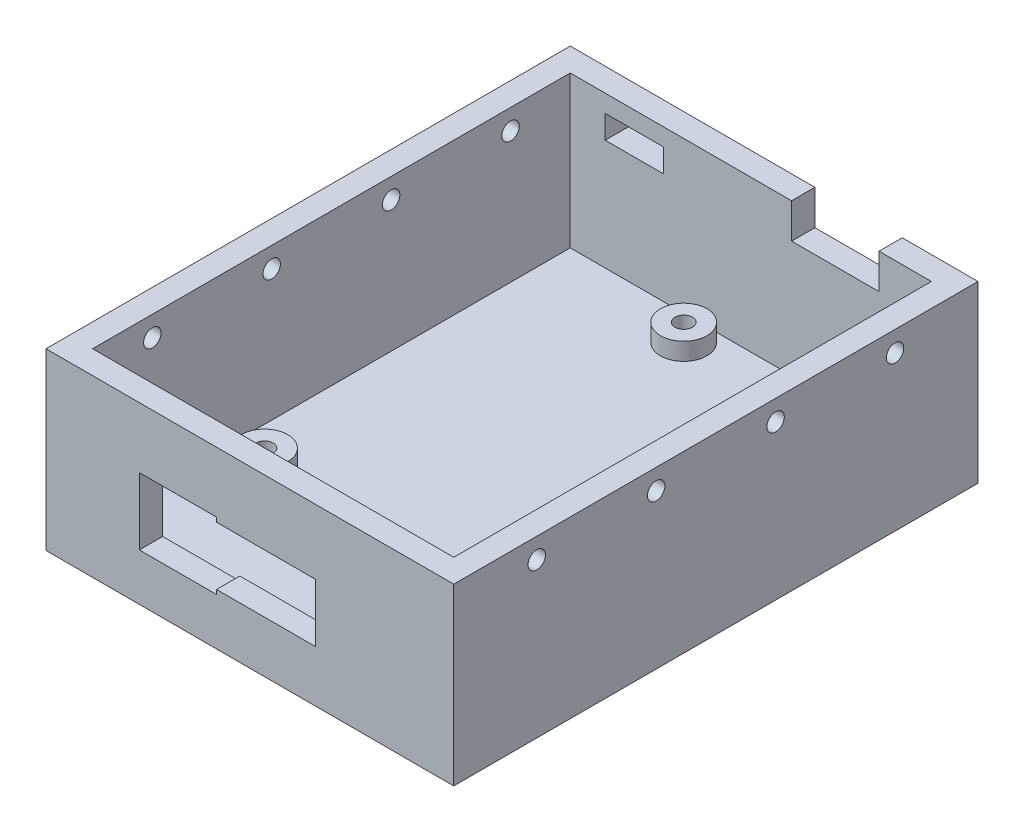
SolidWorks part; units mm, degrees
ref_plane "Front Plane" through (0, 0, 0) normal (0, 0, 1) x (1, 0, 0)
ref_plane "Top Plane" through (0, 0, 0) normal (0, 1, 0) x (1, 0, 0)
ref_plane "Right Plane" through (0, 0, 0) normal (1, 0, 0) x (0, 0, -1)
sketch "Sketch1" plane through (0, 0, 0) normal (0, 1, 0) x (1, 0, 0)
  line L1 (-35, 45) -> (35, 45)
  line L2 (-35, 45) -> (-35, -45)
  line L3 (-35, -45) -> (35, -45)
  line L4 (35, 45) -> (35, -45)
  line L5 (-35, 45) -> (35, -45) construction
  line L6 (-35, -45) -> (35, 45) construction
  point P0 (0, 0)
  dimension "D1" = 70
  dimension "D2" = 90
extrude "Boss-Extrude1" add sketch "Sketch1" along normal blind 30
shell "Shell1" thickness 4
sketch "Sketch2" plane through (0, 0, 45) normal (0, 0, 1) x (1, 0, 0)
  line L4 (-17.9741, 18.6) -> (-17.9741, 9.1)
  line L5 (-17.9741, 9.1) -> (-6.7241, 9.1)
  line L6 (-6.7241, 9.1) -> (-6.7241, 18.6)
  line L7 (-6.7241, 18.6) -> (-17.9741, 18.6)
  line L8 (-17.9741, 18.6) -> (-17.9741, 9.1)
  line L9 (-17.9741, 9.1) -> (-6.7241, 9.1)
  line L10 (-6.7241, 9.1) -> (-6.7241, 18.6)
  line L11 (-6.7241, 18.6) -> (-17.9741, 18.6)
  line L16 (-18.9741, 19.6) -> (-18.9741, 8.1)
  line L17 (-18.9741, 8.1) -> (-5.7241, 8.1)
  line L18 (-5.7241, 8.1) -> (-5.7241, 19.6)
  line L19 (-5.7241, 19.6) -> (-18.9741, 19.6)
  line L20 (-18.9741, 19.6) -> (-18.9741, 8.1)
  line L21 (-18.9741, 8.1) -> (-5.7241, 8.1)
  line L22 (-5.7241, 8.1) -> (-5.7241, 19.6)
  line L23 (-5.7241, 19.6) -> (-18.9741, 19.6)
  dimension "D1" = 0
  dimension "D2" = 1
extrude "Cut-Extrude1" cut sketch "Sketch2" against normal blind 7 contours L22 L23 L20 L21 L11 L10 L9 L8 | L10 L11 L8 L9
sketch "Sketch3" plane through (0, 0, 45) normal (0, 0, 1) x (1, 0, 0)
  line L0 (-5.7241, 13.85) -> (35, 13.85) construction
  line L1 (-5.7241, 8.1) -> (-5.7241, 19.6) construction
  line L2 (35, 30) -> (35, 0) construction
  line L4 (-6.7241, 18.85) -> (11.2759, 18.85)
  line L5 (-6.7241, 18.85) -> (-6.7241, 8.85)
  line L6 (-6.7241, 8.85) -> (11.2759, 8.85)
  line L7 (11.2759, 18.85) -> (11.2759, 8.85)
  line L8 (-6.7241, 18.85) -> (11.2759, 8.85) construction
  line L9 (-6.7241, 8.85) -> (11.2759, 18.85) construction
  point P6 (2.2759, 13.85)
  dimension "D1" = 8
  dimension "D2" = 10
  dimension "D3" = 18
extrude "Cut-Extrude2" cut sketch "Sketch3" against normal blind 7
sketch "Sketch4" plane through (0, 0, -45) normal (0, 0, -1) x (-1, 0, 0)
  line L0 (-35, 30) -> (35, 30) construction
  line L1 (-22, 30) -> (-7, 30)
  line L2 (-22, 30) -> (-22, 24)
  line L3 (-22, 24) -> (-7, 24)
  line L4 (-7, 30) -> (-7, 24)
  line L5 (-35, 30) -> (-35, 0) construction
  dimension "D1" = 13
  dimension "D2" = 6
  dimension "D3" = 15
extrude "Cut-Extrude3" cut sketch "Sketch4" against normal blind 7
sketch "Sketch6" plane through (0, 0, -1.7195) normal (0, -1, 0) x (1, 0, 0)
  circle A4 centre (20.3092, -34.9642) radius 1.5
  circle A5 centre (-7.2071, -34.9642) radius 1.5
  circle A6 centre (25.0259, 19.7358) radius 1.5
  circle A7 centre (-24.4741, 19.7358) radius 1.5
  circle A8 centre (-24.4741, 19.7358) radius 4
  circle A9 centre (25.0259, 19.7358) radius 4
  circle A10 centre (-7.2071, -34.9642) radius 4
  circle A11 centre (20.3092, -34.9642) radius 4
extrude "Boss-Extrude2" add sketch "Sketch6" against normal blind 7 contours A8 A7 | A9 A6 | A11 A4 | A10 A5
sketch "Sketch7" plane through (31, 0, 0) normal (-1, 0, 0) x (0, 0, 1)
  line L0 (0, 30) -> (0, 23) construction
  line L1 (-41, 30) -> (41, 30)
  line L2 (-41, 30) -> (-41, 23)
  line L3 (-41, 23) -> (41, 23)
  line L4 (41, 30) -> (41, 23)
  line L5 (0, 23) -> (-41, 23) construction
  line L6 (-20.5, 23) -> (-20.5, 30) construction
  line L7 (-20.5, 23) -> (-41, 30) construction
  circle A0 centre (-30.75, 26.5) radius 1.5
  circle A1 centre (-10.25, 26.5) radius 1.5
  circle A2 centre (10.25, 26.5) radius 1.5
  circle A3 centre (30.75, 26.5) radius 1.5
  dimension "D2" = 3
  dimension "D1" = 7
extrude "Cut-Extrude4" cut sketch "Sketch7" against normal through all both and the other way through all contours A0 | A1 | A2 | A3
sketch "Sketch8" plane through (0, 0, -45) normal (0, 0, -1) x (-1, 0, 0)
  line L0 (35, 30) -> (35, 0) construction
  line L1 (25, 23) -> (15, 23)
  line L2 (25, 23) -> (25, 27)
  line L3 (25, 27) -> (15, 27)
  line L4 (15, 23) -> (15, 27)
  line L5 (-7, 30) -> (35, 30) construction
  dimension "D1" = 10
  dimension "D2" = 10
  dimension "D3" = 4
  dimension "D4" = 3
extrude "Cut-Extrude5" cut sketch "Sketch8" against normal blind 7
